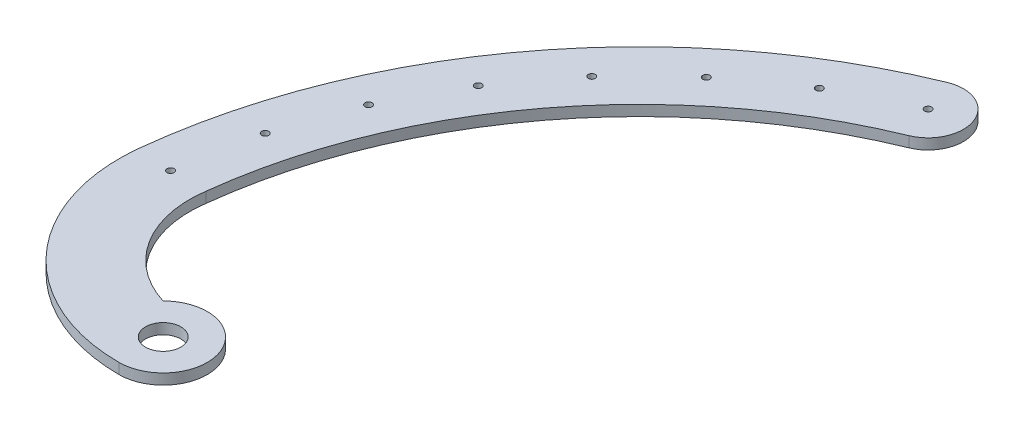
SolidWorks part; units mm, degrees
ref_plane "Ön Düzlem" through (0, 0, 0) normal (0, 0, 1) x (1, 0, 0)
ref_plane "Üst Düzlem" through (0, 0, 0) normal (0, 1, 0) x (1, 0, 0)
ref_plane "Sağ Düzlem" through (0, 0, 0) normal (1, 0, 0) x (0, 0, -1)
sketch "Çizim1" plane through (0, 0, 0) normal (0, 1, 0) x (1, 0, 0)
  line L0 (0, 87.5) -> (50, 174.1025) construction
  line L2 (0, 0) -> (0, 87.5) construction
  line L4 (-5, 21.3624) -> (-5, 8.6603) construction
  line L5 (5, 16.8404) -> (5, 8.6603) construction
  circle A0 centre (0, 0) radius 50 construction
  circle A1 centre (0, 87.5) radius 100 construction
  circle A2 centre (0, 0) radius 12.5
  circle A3 centre (0, 0) radius 5
  arc A4 (50, 174.1025) -> (0, 12.5) centre (-99.0854, 131.6934) cw construction
  arc A6 (-39.7619, 41.8581) -> (52.4452, 164.3044) centre (109.3452, 25.5154) cw construction
  circle A9 centre (0, 36.3607) radius 17.5 construction
  arc A10 (48.6518, 173.557) -> (-49.7024, 42.9476) centre (109.3452, 25.5154) ccw
  arc A11 (-49.7024, 42.9476) -> (0, -12.5) centre (0, 37.5) ccw
  circle A12 centre (52.4452, 164.3044) radius 10
  arc A13 (-29.6977, 41.8581) -> (56.2385, 155.0518) centre (109.3452, 25.5154) cw
  arc A14 (-39.7619, 41.8581) -> (0, -2.5) centre (0, 37.5) ccw construction
  arc A15 (43.1054, 160.0973) -> (-5, 21.3624) centre (-99.0854, 131.6934) cw construction
  arc A16 (50, 174.1025) -> (5, 16.8404) centre (-99.0854, 131.6934) cw construction
  arc A17 (43.1054, 160.0973) -> (-39.7619, 41.8581) centre (109.3452, 25.5154) ccw construction
  arc A18 (-29.6977, 41.8581) -> (-8.8569, 8.8207) centre (0, 37.5) ccw
  circle A19 centre (52.4452, 164.3044) radius 1
  circle A20 centre (31.9294, 153.9941) radius 1
  circle A21 centre (13.2275, 140.6735) radius 1
  circle A22 centre (-3.2222, 124.6546) radius 1
  circle A23 centre (-17.0343, 106.3128) radius 1
  circle A24 centre (-27.8853, 86.0778) radius 1
  circle A25 centre (-35.5207, 64.4238) radius 1
  circle A26 centre (-39.7619, 41.8581) radius 1
  arc A27 (-49.7024, 42.9476) -> (0, -12.5) centre (0, 37.5) ccw construction
  arc A28 (50, 174.1025) -> (-49.7024, 42.9476) centre (109.3452, 25.5154) ccw construction
  point P48 (109.3452, 25.5154)
  dimension "D1" = 100
  dimension "D2" = 200
  dimension "D3" = 25
  dimension "D4" = 10
  dimension "D6" = 155
  dimension "D8" = 2
  dimension "D9" = 35
  dimension "D10" = 160
  dimension "D7" = 50
  dimension "D5" = 150
  dimension "D11" = 10
extrude "Yükseklik-Ekstrüzyon1" add sketch "Çizim1" along normal blind 3 contours A18 A13 A12 A10 A11 A2 A26 A25 A24 A23 A22 A21 A20 | A2 A3 | A12 A19
